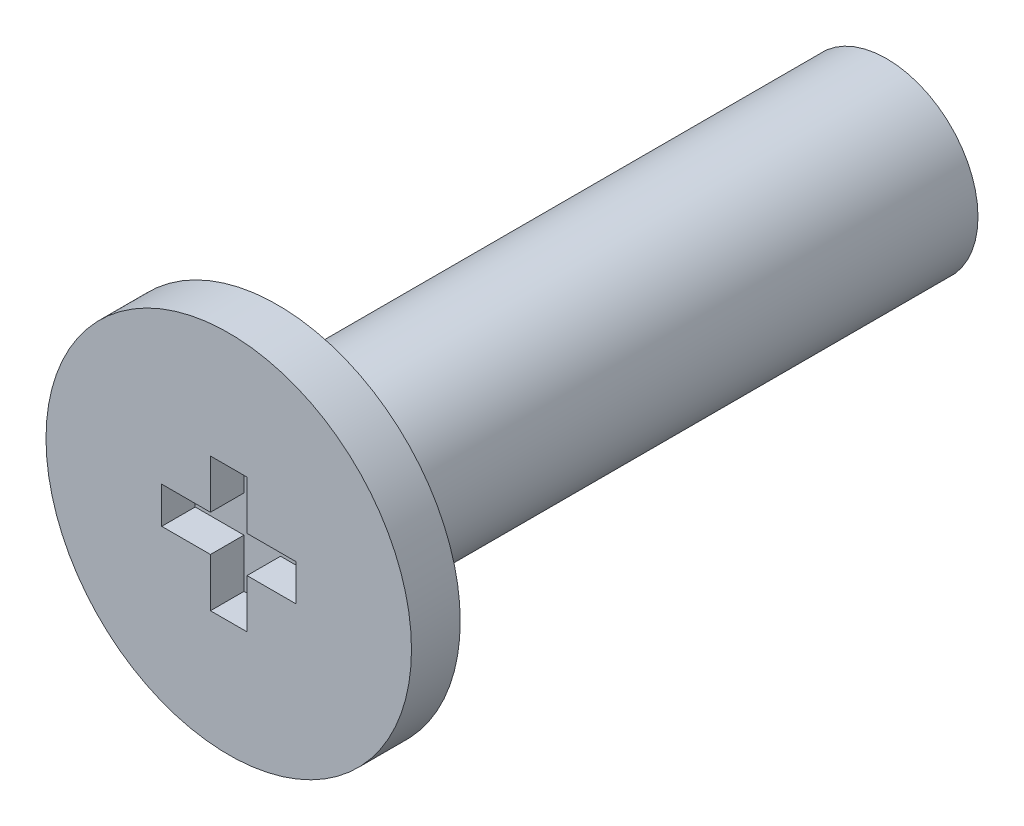
SolidWorks part; units mm, degrees
ref_plane "前视基准面" through (0, 0, 0) normal (0, 0, 1) x (1, 0, 0)
ref_plane "上视基准面" through (0, 0, 0) normal (0, 1, 0) x (1, 0, 0)
ref_plane "右视基准面" through (0, 0, 0) normal (1, 0, 0) x (0, 0, -1)
other "Configuration Table"
sketch "草图1" plane through (0, 0, 0) normal (0, 0, 1) x (1, 0, 0)
  circle A0 centre (0, 0) radius 1.5
extrude "标准杆径_头下长度" add sketch "草图1" against normal blind 10
sketch "草图2" plane through (0, 0, 0) normal (0, 0, 1) x (1, 0, 0)
  circle A0 centre (0, 0) radius 2.75
sketch "草图4" plane through (0, 0, 0) normal (0, 1, 0) x (1, 0, 0)
  line L0 (0, 0) -> (3.45, 0)
  line L1 (3.45, 0) -> (3.45, -0.3426)
  line L2 (0, -1.9) -> (0, 0)
  line L3 (0, 2) -> (0, -3.9) construction
  arc A0 (3.45, -0.3426) -> (0, -1.9) centre (0, 2.7) cw
sketch "草图5" plane through (0, 0, 0) normal (0, 0, 1) x (1, 0, 0)
  line L0 (-0.3, -1.45) -> (0.3, -1.45)
  line L1 (0.3, -1.45) -> (0.3, -0.3)
  line L2 (0.3, -0.3) -> (1.45, -0.3)
  line L3 (1.45, -0.3) -> (1.45, 0.3)
  line L4 (1.45, 0.3) -> (0.3, 0.3)
  line L5 (0.3, 0.3) -> (0.3, 1.45)
  line L6 (0.3, 1.45) -> (-0.3, 1.45)
  line L7 (-0.3, 1.45) -> (-0.3, 0.3)
  line L8 (-0.3, 0.3) -> (-1.45, 0.3)
  line L9 (-1.45, 0.3) -> (-1.45, -0.3)
  line L10 (-1.45, -0.3) -> (-0.3, -0.3)
  line L11 (-0.3, -0.3) -> (-0.3, -1.45)
sketch "草图6" plane through (0, 0, 0) normal (0, 1, 0) x (1, 0, 0)
  line L0 (0, 0) -> (3, 0)
  line L1 (3, 0) -> (3, -0.8)
  line L2 (3, -0.8) -> (0, -0.8)
  line L3 (0, -0.8) -> (0, 0)
  line L4 (0, 2) -> (0, -2.8) construction
revolve "已确认_十字槽超薄头" add sketch "草图6" angle 360 about L4
sketch "草图7" plane through (0, 0, 0) normal (0, 0, 1) x (1, 0, 0)
  line L0 (-0.3, -1.1) -> (0.3, -1.1)
  line L1 (0.3, -1.1) -> (0.3, -0.3)
  line L2 (0.3, -0.3) -> (1.1, -0.3)
  line L3 (1.1, -0.3) -> (1.1, 0.3)
  line L4 (1.1, 0.3) -> (0.3, 0.3)
  line L5 (0.3, 0.3) -> (0.3, 1.1)
  line L6 (0.3, 1.1) -> (-0.3, 1.1)
  line L7 (-0.3, 1.1) -> (-0.3, 0.3)
  line L8 (-0.3, 0.3) -> (-1.1, 0.3)
  line L9 (-1.1, 0.3) -> (-1.1, -0.3)
  line L10 (-1.1, -0.3) -> (-0.3, -0.3)
  line L11 (-0.3, -0.3) -> (-0.3, -1.1)
extrude "十字槽_PH1_简化" cut sketch "草图7" against normal blind 0.56 from offset 0.81
